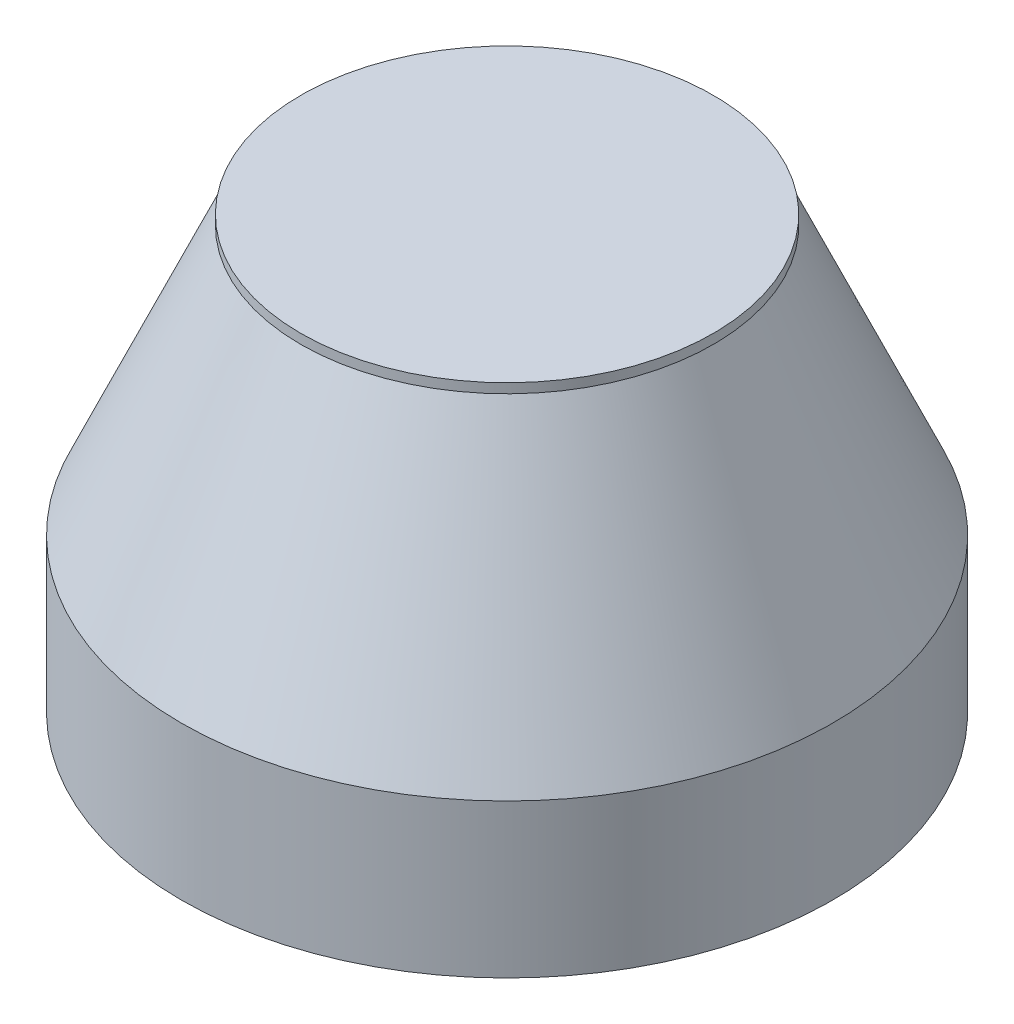
SolidWorks part; units mm, degrees
ref_plane "前视基准面" through (0, 0, 0) normal (0, 0, 1) x (1, 0, 0)
ref_plane "上视基准面" through (0, 0, 0) normal (0, 1, 0) x (1, 0, 0)
ref_plane "右视基准面" through (0, 0, 0) normal (1, 0, 0) x (0, 0, -1)
other "Configuration Table"
sketch "草图1" plane through (0, 0, 0) normal (0, 1, 0) x (1, 0, 0)
  circle A0 centre (0, 0) radius 17
extrude "凸台-拉伸1" add sketch "草图1" along normal blind 8
sketch "草图2" plane through (0, 8, 0) normal (0, 1, 0) x (1, 0, 0)
  circle A0 centre (0, 0) radius 17
extrude "凸台-拉伸2" add sketch "草图2" along normal blind 14 draft 24
sketch "草图4" plane through (0, 22, 0) normal (0, 1, 0) x (1, 0, 0)
  circle A0 centre (0, 0) radius 10.7668
extrude "凸台-拉伸3" add sketch "草图4" along normal blind 0.5
